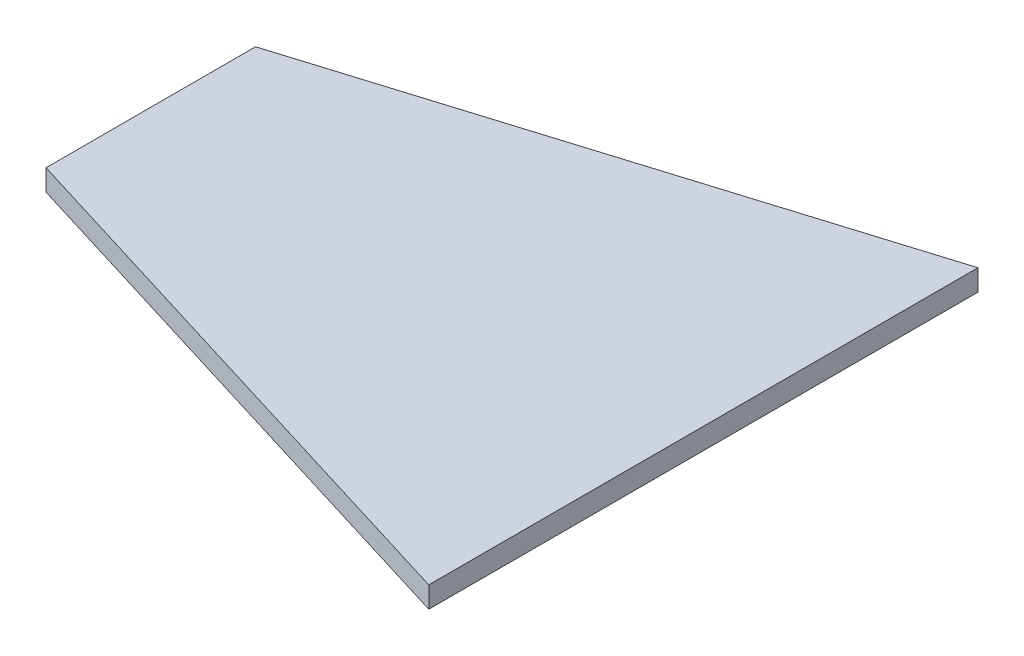
SolidWorks part; units mm, degrees
ref_plane "Front Plane" through (0, 0, 0) normal (0, 0, 1) x (1, 0, 0)
ref_plane "Top Plane" through (0, 0, 0) normal (0, 1, 0) x (1, 0, 0)
ref_plane "Right Plane" through (0, 0, 0) normal (1, 0, 0) x (0, 0, -1)
sketch "Sketch1" plane through (0, 0, 0) normal (0, 1, 0) x (1, 0, 0)
  line L0 (0, 0) -> (0, 82.55)
  line L1 (0, 82.55) -> (-83.058, 57.023)
  line L2 (-83.058, 57.023) -> (-83.058, 25.527)
  line L3 (-83.058, 25.527) -> (0, 0)
  dimension "D1" = 31.496
  dimension "D2" = 83.058
  dimension "D3" = 82.55
extrude "Boss-Extrude1" add sketch "Sketch1" along normal blind 3.175
